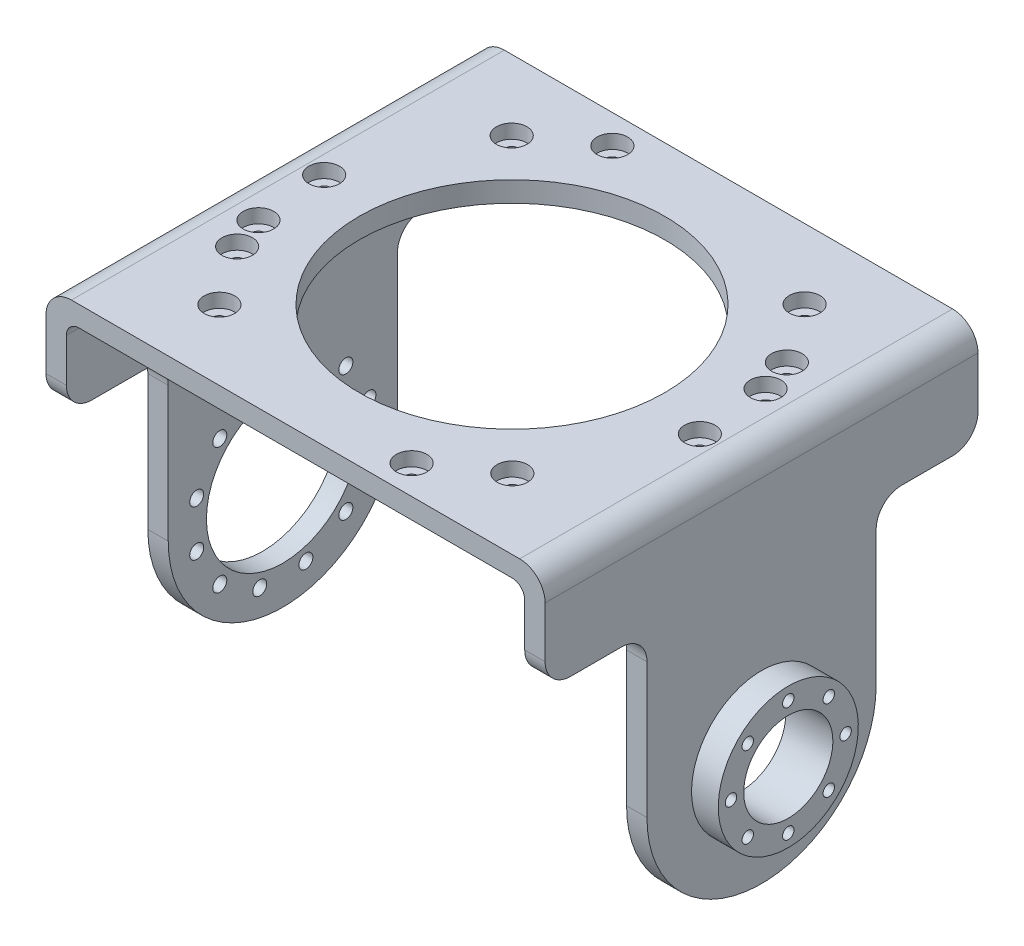
SolidWorks part; units mm, degrees
material "6061 合金"
ref_plane "前视基准面" through (0, 0, 0) normal (0, 0, 1) x (1, 0, 0)
ref_plane "上视基准面" through (0, 0, 0) normal (0, 1, 0) x (1, 0, 0)
ref_plane "右视基准面" through (0, 0, 0) normal (1, 0, 0) x (0, 0, -1)
other "Configuration Table"
sketch "草图1" plane through (0, 0, 0) normal (0, 0, 1) x (1, 0, 0)
  line L0 (-180, 0) -> (0, 0)
  line L1 (0, 0) -> (0, -175)
  line L3 (8, -175) -> (8, 8)
  line L4 (8, 8) -> (-180, 8)
  line L6 (0, -175) -> (8, -175)
  line L12 (-180, 8) -> (-188, 8)
  line L13 (-180, 0) -> (-180, -175)
  line L14 (-180, -175) -> (-188, -175)
  line L15 (-188, 8) -> (-188, -175)
  dimension "D1" = 8
  dimension "D2" = 8
  dimension "D4" = 180
  dimension "D5" = 183
  dimension "D6" = 8
  dimension "D8" = 8
extrude "凸台-拉伸1" add sketch "草图1" along normal blind 170
sketch "草图2" plane through (0, 8, 0) normal (0, 1, 0) x (1, 0, 0)
  line L0 (-216.3195, -85) -> (51.5119, -85) construction
  line L1 (8, -170) -> (-188, -170) construction
  line L2 (8, 0) -> (-188, 0) construction
  line L7 (-90, -75.3242) -> (-90, -92.2023) construction
  line L8 (8, -170) -> (8, 0) construction
  line L9 (-188, -170) -> (-188, 0) construction
  circle A2 centre (-90, -85) radius 60
  dimension "D3" = 120
extrude "切除-拉伸1" cut sketch "草图2" against normal blind 180 contours A2 L0 | L0 A2
sketch "草图3" plane through (8, 0, 0) normal (1, 0, 0) x (0, 0, -1)
  line L0 (-85, 25.6845) -> (-85, -173.3318) construction
  line L1 (0, -175) -> (0, 8) construction
  line L2 (-170, -175) -> (-170, 8) construction
  line L3 (-170, -175) -> (0, -175) construction
  line L4 (0, 0) -> (-209.686, 0) construction
  circle A0 centre (-85, -95) radius 17.5
  dimension "D1" = 35
  dimension "D2" = 80
extrude "切除-拉伸2" cut sketch "草图3" against normal through all both and the other way through all contours A0
fillet "圆角1" radius 70 4 edges at (-184, -175, 170) (-184, -175, 0) (4, -175, 0) (4, -175, 170)
fillet "圆角2" radius 5 2 edges at (-180, 0, 85) (0, 0, 85)
fillet "圆角3" radius 10 2 edges at (8, 8, 85) (-188, 8, 85)
sketch "草图6" plane through (-188, 0, 0) normal (-1, 0, 0) x (0, 0, 1)
  circle A0 centre (85, -95) radius 30
  dimension "D1" = 60
extrude "切除-拉伸6" cut sketch "草图6" against normal blind 39
sketch "草图7" plane through (0, 0, 0) normal (-1, 0, 0) x (0, 0, 1)
  circle A0 centre (85, -95) radius 13
  dimension "D1" = 26
extrude "切除-拉伸7" [suppressed] cut sketch "草图7" against normal blind 0.7
sketch "草图8" plane through (8, 0, 0) normal (1, 0, 0) x (0, 0, -1)
  line L0 (-85, -95) -> (-13.3452, -95) construction
  line L1 (-85, -95) -> (-143.0331, -95) construction
  circle A0 centre (-55, -95) radius 2.5
  circle A1 centre (-115, -95) radius 2.5
  dimension "D1" = 5
  dimension "D2" = 5
  dimension "D3" = 30
  dimension "D4" = 30
extrude "切除-拉伸8" [suppressed] cut sketch "草图8" against normal blind 10
sketch "草图9" [suppressed] plane through (8, 0, 0) normal (1, 0, 0) x (0, 0, -1)
  circle A0 centre (-55, -95) radius 6
  circle A1 centre (-115, -95) radius 6
  dimension "D1" = 12
  dimension "D2" = 12
extrude "切除-拉伸9" [suppressed] cut sketch "草图9" against normal blind 4
sketch "草图10" plane through (0, 0, 0) normal (0, -1, 0) x (1, 0, 0)
  arc A0 (-173.1989, 76.7742) -> (-168.6673, 78.8872) centre (-170.9331, 77.8307) ccw construction
  arc A1 (-149.7806, 26.5535) -> (-145.249, 28.6665) centre (-147.5148, 27.61) ccw construction
  arc A2 (-126.5235, 10.2687) -> (-121.992, 12.3818) centre (-124.2577, 11.3252) ccw construction
  arc A3 (-113.38, 5.4849) -> (-108.8485, 7.598) centre (-111.1143, 6.5414) ccw construction
  arc A4 (-85.0965, 3.0104) -> (-80.5649, 5.1235) centre (-82.8307, 4.0669) ccw construction
  arc A5 (-34.8758, 26.4287) -> (-30.3442, 28.5418) centre (-32.61, 27.4852) ccw construction
  arc A6 (-13.8072, 62.8292) -> (-9.2756, 64.9423) centre (-11.5414, 63.8857) ccw construction
  arc A7 (-18.591, 49.6857) -> (-14.0595, 51.7988) centre (-16.3252, 50.7423) ccw construction
  arc A8 (-6.8011, 93.2258) -> (-11.3327, 91.1128) centre (-9.0669, 92.1693) ccw construction
  arc A9 (-30.2194, 143.4465) -> (-34.751, 141.3335) centre (-32.4852, 142.39) ccw construction
  arc A10 (-53.4765, 159.7313) -> (-58.008, 157.6182) centre (-55.7423, 158.6748) ccw construction
  arc A11 (-66.62, 164.5151) -> (-71.1515, 162.402) centre (-68.8857, 163.4586) ccw construction
  arc A12 (-94.9035, 166.9896) -> (-99.4351, 164.8765) centre (-97.1693, 165.9331) ccw construction
  arc A13 (-145.1242, 143.5713) -> (-149.6558, 141.4582) centre (-147.39, 142.5148) ccw construction
  arc A14 (-161.409, 120.3143) -> (-165.9405, 118.2012) centre (-163.6748, 119.2577) ccw construction
  arc A15 (-166.1928, 107.1708) -> (-170.7244, 105.0577) centre (-168.4586, 106.1143) ccw construction
  arc A16 (-173.1989, 76.7742) -> (-168.6673, 78.8872) centre (-170.9331, 77.8307) ccw construction
  arc A17 (-149.7806, 26.5535) -> (-145.249, 28.6665) centre (-147.5148, 27.61) ccw construction
  arc A18 (-126.5235, 10.2687) -> (-121.992, 12.3818) centre (-124.2577, 11.3252) ccw construction
  arc A19 (-113.38, 5.4849) -> (-108.8485, 7.598) centre (-111.1143, 6.5414) ccw construction
  arc A20 (-85.0965, 3.0104) -> (-80.5649, 5.1235) centre (-82.8307, 4.0669) ccw construction
  arc A21 (-34.8758, 26.4287) -> (-30.3442, 28.5418) centre (-32.61, 27.4852) ccw construction
  arc A22 (-13.8072, 62.8292) -> (-9.2756, 64.9423) centre (-11.5414, 63.8857) ccw construction
  arc A23 (-18.591, 49.6857) -> (-14.0595, 51.7988) centre (-16.3252, 50.7423) ccw construction
  arc A24 (-6.8011, 93.2258) -> (-11.3327, 91.1128) centre (-9.0669, 92.1693) ccw construction
  arc A25 (-30.2194, 143.4465) -> (-34.751, 141.3335) centre (-32.4852, 142.39) ccw construction
  arc A26 (-53.4765, 159.7313) -> (-58.008, 157.6182) centre (-55.7423, 158.6748) ccw construction
  arc A27 (-66.62, 164.5151) -> (-71.1515, 162.402) centre (-68.8857, 163.4586) ccw construction
  arc A28 (-94.9035, 166.9896) -> (-99.4351, 164.8765) centre (-97.1693, 165.9331) ccw construction
  arc A29 (-145.1242, 143.5713) -> (-149.6558, 141.4582) centre (-147.39, 142.5148) ccw construction
  arc A30 (-161.409, 120.3143) -> (-165.9405, 118.2012) centre (-163.6748, 119.2577) ccw construction
  arc A31 (-166.1928, 107.1708) -> (-170.7244, 105.0577) centre (-168.4586, 106.1143) ccw construction
  circle A32 centre (-32.4852, 142.39) radius 2.5
  circle A33 centre (-55.7423, 158.6748) radius 2.5
  circle A34 centre (-68.8857, 163.4586) radius 2.5
  circle A35 centre (-147.39, 142.5148) radius 2.5
  circle A36 centre (-163.6748, 119.2577) radius 2.5
  circle A37 centre (-168.4586, 106.1143) radius 2.5
  circle A38 centre (-170.9331, 77.8307) radius 2.5
  circle A40 centre (-147.5148, 27.61) radius 2.5
  circle A41 centre (-124.2577, 11.3252) radius 2.5
  circle A42 centre (-111.1143, 6.5414) radius 2.5
  circle A44 centre (-32.61, 27.4852) radius 2.5
  circle A45 centre (-16.3252, 50.7423) radius 2.5
  circle A46 centre (-11.5414, 63.8857) radius 2.5
  circle A47 centre (-9.0669, 92.1693) radius 2.5
  dimension "D1" = 5
extrude "切除-拉伸10" cut sketch "草图10" against normal blind 10 contours A33 | A32 | A47 | A46 | A45 | A44 | A41 | A40 | A38 | A37 | A36 | A35
sketch "草图11" plane through (0, 8, 0) normal (0, 1, 0) x (1, 0, 0)
  circle A1 centre (-32.61, -27.4852) radius 6
  circle A2 centre (-16.3252, -50.7423) radius 6
  circle A3 centre (-11.5414, -63.8857) radius 6
  circle A4 centre (-9.0669, -92.1693) radius 6
  circle A5 centre (-32.4852, -142.39) radius 6
  circle A6 centre (-55.7423, -158.6748) radius 6
  circle A8 centre (-147.39, -142.5148) radius 6
  circle A9 centre (-163.6748, -119.2577) radius 6
  circle A10 centre (-168.4586, -106.1143) radius 6
  circle A11 centre (-170.9331, -77.8307) radius 6
  circle A12 centre (-147.5148, -27.61) radius 6
  circle A13 centre (-124.2577, -11.3252) radius 6
  circle M2 centre (-55.7423, -158.6748) radius 2.5
  circle M4 centre (-147.39, -142.5148) radius 2.5
  circle M5 centre (-163.6748, -119.2577) radius 2.5
  circle M6 centre (-168.4586, -106.1143) radius 2.5
  circle M7 centre (-170.9331, -77.8307) radius 2.5
  circle M8 centre (-147.5148, -27.61) radius 2.5
  circle M9 centre (-124.2577, -11.3252) radius 2.5
  circle M11 centre (-32.61, -27.4852) radius 2.5
  circle M12 centre (-16.3252, -50.7423) radius 2.5
  circle M13 centre (-11.5414, -63.8857) radius 2.5
  circle M14 centre (-9.0669, -92.1693) radius 2.5
  circle M15 centre (-32.4852, -142.39) radius 2.5
  dimension "D1" = 12
extrude "切除-拉伸11" cut sketch "草图11" against normal blind 5.5 contours A5 M15 | A6 M2 | A8 M4 | A9 M5 | A10 M6 | A11 M7 | A12 M8 | A13 M9 | A1 M11 | A2 M12 | A3 M13 | A4 M14
sketch "草图12" plane through (-188, 0, 0) normal (-1, 0, 0) x (0, 0, 1)
  line L0 (85, -95) -> (85, -143.8801) construction
  line L1 (85, -95) -> (97.9809, -143.4455) construction
  circle A0 centre (94.0587, -128.8074) radius 2.75
  circle A1 centre (75.9413, -128.8074) radius 2.75
  circle A2 centre (60.2513, -119.7487) radius 2.75
  circle A3 centre (51.1926, -104.0587) radius 2.75
  circle A4 centre (51.1926, -85.9413) radius 2.75
  circle A5 centre (60.2513, -70.2513) radius 2.75
  circle A6 centre (75.9413, -61.1926) radius 2.75
  circle A7 centre (94.0587, -61.1926) radius 2.75
  circle A8 centre (109.7487, -70.2513) radius 2.75
  circle A9 centre (118.8074, -85.9413) radius 2.75
  circle A10 centre (118.8074, -104.0587) radius 2.75
  circle A11 centre (109.7487, -119.7487) radius 2.75
  point P31 (85, -95)
  dimension "D2" = 5.5
  dimension "D1" = 15
  dimension "D3" = 35
  dimension "D4" = 12
extrude "切除-拉伸12" cut sketch "草图12" against normal blind 10
sketch "草图14" plane through (8, 0, 0) normal (1, 0, 0) x (0, 0, -1)
  circle A0 centre (-85, -95) radius 27.5
  circle A1 centre (-85, -95) radius 17.5 construction
  circle A2 centre (-85, -95) radius 17.5
  dimension "D1" = 55
extrude "凸台-拉伸2" add sketch "草图14" along normal blind 10.5
sketch "草图13" plane through (8, 0, 0) normal (1, 0, 0) x (0, 0, -1)
  line L0 (-85, -95) -> (-85, -50) construction
  circle A0 centre (-85, -95) radius 22.5 construction
  circle A1 centre (-85, -72.5) radius 2.25
  circle A2 centre (-69.0901, -79.0901) radius 2.25
  circle A3 centre (-62.5, -95) radius 2.25
  circle A4 centre (-69.0901, -110.9099) radius 2.25
  circle A5 centre (-85, -117.5) radius 2.25
  circle A6 centre (-100.9099, -110.9099) radius 2.25
  circle A7 centre (-107.5, -95) radius 2.25
  circle A8 centre (-100.9099, -79.0901) radius 2.25
  point P22 (-85, -95)
  dimension "D1" = 45
  dimension "D2" = 4.5
  dimension "D3" = 8
extrude "切除-拉伸13" cut sketch "草图13" against normal mid plane 30
sketch "草图15" plane through (-188, 0, 0) normal (-1, 0, 0) x (0, 0, 1)
  line L0 (85, 14.6274) -> (85, -188.8323) construction
  line L1 (170, -2) -> (170, -105) construction
  line L2 (0, -2) -> (0, -105) construction
  line L3 (0, -32) -> (40, -32)
  line L4 (40, -32) -> (40, -95)
  line L5 (100, -175) -> (70, -175) construction
  line L6 (0, 8) -> (170, 8) construction
  line L7 (170, -32) -> (170, -105)
  line L8 (100, -175) -> (70, -175)
  line L9 (0, -32) -> (0, -105)
  line L10 (130, -32) -> (130, -95)
  line L11 (170, -32) -> (130, -32)
  arc A0 (40, -95) -> (130, -95) centre (85, -95) ccw
  arc A1 (100, -175) -> (170, -105) centre (100, -105) ccw construction
  arc A2 (0, -105) -> (70, -175) centre (70, -105) ccw construction
  arc A3 (100, -175) -> (170, -105) centre (100, -105) ccw
  arc A4 (0, -105) -> (70, -175) centre (70, -105) ccw
  dimension "D1" = 40
  dimension "D2" = 40
extrude "切除-拉伸14" cut sketch "草图15" against normal blind 262
fillet "圆角4" radius 10 8 edges at (4, -32, 0) (4, -32, 40) (4, -32, 130) (4, -32, 170) (-184, -32, 0) (-184, -32, 40) (-184, -32, 130) (-184, -32, 170)
